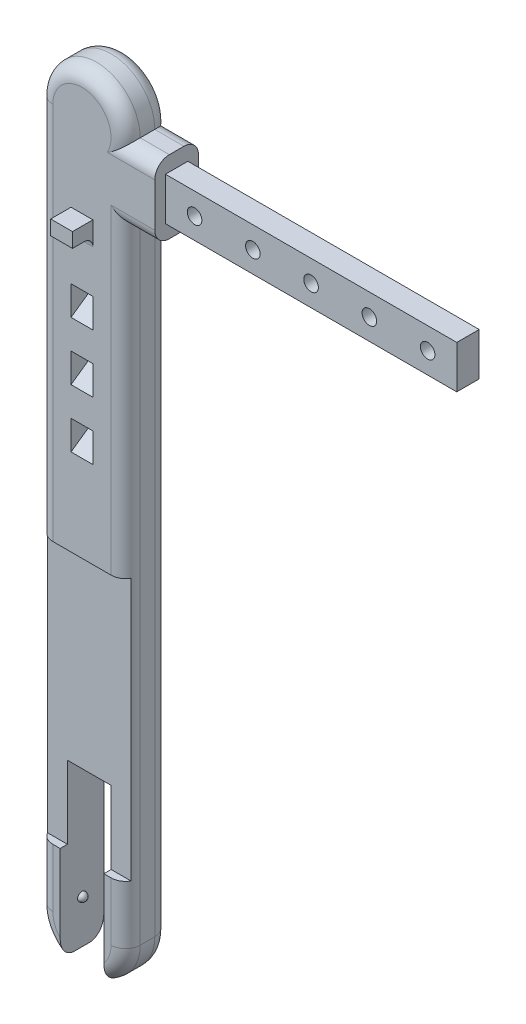
SolidWorks part; units mm, degrees
ref_plane "Front Plane" through (0, 0, 0) normal (0, 0, 1) x (1, 0, 0)
ref_plane "Top Plane" through (0, 0, 0) normal (0, 1, 0) x (1, 0, 0)
ref_plane "Right Plane" through (0, 0, 0) normal (1, 0, 0) x (0, 0, -1)
sketch "Sketch1" plane through (0, 0, 0) normal (0, 0, 1) x (1, 0, 0)
  line L0 (0, 124.9367) -> (0, -115.0633) construction
  line L1 (15, 99.9367) -> (15, -115.0633)
  line L2 (-15, 124.9367) -> (-15, -115.0633)
  line L3 (15, 124.9367) -> (25, 124.9367)
  line L4 (25, 124.9367) -> (25, 99.9367)
  line L5 (25, 99.9367) -> (15, 99.9367)
  arc A0 (15, 124.9367) -> (-15, 124.9367) centre (0, 124.9367) ccw
  arc A1 (-15, -115.0633) -> (15, -115.0633) centre (0, -115.0633) ccw
  point P3 (0, 4.9367)
  dimension "D2" = 15
  dimension "D1" = 240
  dimension "D3" = 10
  dimension "D4" = 25
extrude "Boss-Extrude1" add sketch "Sketch1" along normal mid plane 15
fillet "Fillet1" radius 5 12 edges at (0, 139.9367, -7.5) (-15, 4.9367, -7.5) (0, -130.0633, -7.5) (0, 139.9367, 7.5) (-15, 4.9367, 7.5) (0, -130.0633, 7.5) (20, 99.9367, -7.5) (20, 124.9367, -7.5) (20, 124.9367, 7.5) (20, 99.9367, 7.5) (15, -7.5633, -7.5) (15, -7.5633, 7.5)
sketch "Sketch2" plane through (25, 0, 0) normal (1, 0, 0) x (0, 0, -1)
  line L0 (7.5, 104.9367) -> (7.5, 119.9367) construction
  line L1 (-3.85, 119.7867) -> (3.85, 119.7867)
  line L2 (-3.85, 119.7867) -> (-3.85, 105.0867)
  line L3 (-3.85, 105.0867) -> (3.85, 105.0867)
  line L4 (3.85, 119.7867) -> (3.85, 105.0867)
  line L5 (-2.5, 124.9367) -> (2.5, 124.9367) construction
  dimension "D1" = 7.7
  dimension "D2" = 14.7
  dimension "D3" = 3.65
  dimension "D4" = 5.15
extrude "Boss-Extrude2" add sketch "Sketch2" along normal blind 100
sketch "Sketch3" plane through (0, 0, 3.85) normal (0, 0, 1) x (1, 0, 0)
  line L0 (25, 104.9367) -> (25, 119.9367) construction
  line L1 (125, 119.7867) -> (25, 119.7867) construction
  circle A0 centre (35, 112.3367) radius 2.5
  circle A1 centre (55, 112.3367) radius 2.5
  circle A2 centre (75, 112.3367) radius 2.5
  circle A3 centre (95, 112.3367) radius 2.5
  circle A4 centre (115, 112.3367) radius 2.5
  dimension "D2" = 5
  dimension "D1" = 10
  dimension "D3" = 7.45
  dimension "D4" = 5
extrude "Cut-Extrude1" cut sketch "Sketch3" against normal blind 100
sketch "Sketch4" plane through (0, 0, 7.5) normal (0, 0, 1) x (1, 0, 0)
  line L0 (-10, 124.9367) -> (-10, -115.0633) construction
  line L1 (-7.5, -130.0633) -> (7.5, -130.0633)
  line L2 (-7.5, -130.0633) -> (-7.5, -70.0633)
  line L3 (-7.5, -70.0633) -> (7.5, -70.0633)
  line L4 (7.5, -130.0633) -> (7.5, -70.0633)
  arc A0 (-15, -115.0633) -> (15, -115.0633) centre (0, -115.0633) ccw construction
  dimension "D1" = 60
  dimension "D2" = 15
  dimension "D3" = 2.5
extrude "Cut-Extrude2" cut sketch "Sketch4" against normal blind 100
sketch "Sketch7" plane through (0, 0, 0) normal (1, 0, 0) x (0, 0, -1)
  line L1 (-7.5, 124.9367) -> (-7.5, -115.0633) construction
  line L5 (0, -41.6141) -> (0, 18.3597) construction
  line L6 (0, 69.9367) -> (-7.5, 64.6852)
  line L7 (0, 79.9367) -> (-7.5, 74.6852)
  line L8 (-7.5, 74.6852) -> (-7.5, 64.6852)
  line L10 (0, 69.9367) -> (0, 79.9367)
  line L11 (0, 49.9367) -> (0, 59.9367)
  line L12 (0, 59.9367) -> (-7.5, 54.6852)
  line L13 (-7.5, 54.6852) -> (-7.5, 44.6852)
  line L14 (-7.5, 44.6852) -> (0, 49.9367)
  line L15 (0, 29.9367) -> (0, 39.9367)
  line L16 (0, 39.9367) -> (-7.5, 34.6852)
  line L17 (-7.5, 34.6852) -> (-7.5, 24.6852)
  line L18 (-7.5, 24.6852) -> (0, 29.9367)
  line L23 (-2.5, 124.9367) -> (2.5, 124.9367) construction
  line L24 (0, 9.9367) -> (0, 19.9367) [skipped]
  line L25 (0, 19.9367) -> (-7.5, 14.6852) [skipped]
  line L26 (-7.5, 14.6852) -> (-7.5, 4.6852) [skipped]
  dimension "D1" = 45
  dimension "D2" = 10
  dimension "D6" = 55
  dimension "D8" = 4
extrude "Cut-Extrude3" cut sketch "Sketch7" against normal mid plane 7.5
sketch "Sketch8" plane through (0, 0, 0) normal (0, 0, 1) x (1, 0, 0)
  line L0 (-28.1388, -113.0633) -> (31.3541, -113.0633) construction
  line L1 (7.5, -70.0633) -> (-7.5, -70.0633) construction
  line L2 (-7.5, -113.0633) -> (-6, -113.0633)
  line L3 (-7.5, -70.0633) -> (-7.5, -121.6777) construction
  line L4 (-7.5, -111.5633) -> (-7.5, -113.0633)
  line L5 (7.5, -113.0633) -> (6, -113.0633)
  line L6 (7.5, -121.6777) -> (7.5, -70.0633) construction
  line L7 (7.5, -111.5633) -> (7.5, -113.0633)
  arc A0 (-6, -113.0633) -> (-7.5, -111.5633) centre (-7.5, -113.0633) ccw
  arc A1 (6, -113.0633) -> (7.5, -111.5633) centre (7.5, -113.0633) cw
  dimension "D1" = 43
  dimension "D2" = 1.5
  dimension "D3" = 1.5
revolve "Revolve1" add sketch "Sketch8" angle 360 about L0
sketch "Sketch9" plane through (0, 0, 0) normal (1, 0, 0) x (0, 0, -1)
  line L0 (-7.5, 89.4367) -> (-7.5, 97.4367)
  line L1 (-7.5, 124.9367) -> (-7.5, -115.0633) construction
  line L2 (-7.5, 97.4367) -> (-14.5, 97.4367)
  line L3 (-14.5, 97.4367) -> (-14.5, 92.4367)
  line L5 (-14.5, 92.4367) -> (-10.5, 92.4367)
  arc A2 (-10.5, 92.4367) -> (-7.5, 89.4367) centre (-10.5, 89.4367) cw
  dimension "D4" = 3
  dimension "D1" = 15.5
  dimension "D2" = 7
  dimension "D3" = 5
extrude "Boss-Extrude3" add sketch "Sketch9" along normal mid plane 7.5
sketch "Sketch10" plane through (-15, 0, 0) normal (-1, 0, 0) x (0, 0, 1)
  line L0 (7.5, -95.0633) -> (5, -95.0633)
  line L1 (7.5, 124.9367) -> (7.5, -115.0633) construction
  line L2 (5, -95.0633) -> (5, -5.0633)
  line L3 (5, -5.0633) -> (7.5, -5.0633)
  line L4 (7.5, -5.0633) -> (7.5, -95.0633)
  line L5 (2.5, -115.0633) -> (7.5, -115.0633) construction
  dimension "D1" = 2.5
  dimension "D2" = 90
  dimension "D3" = 20
extrude "Cut-Extrude4" cut sketch "Sketch10" against normal through all
